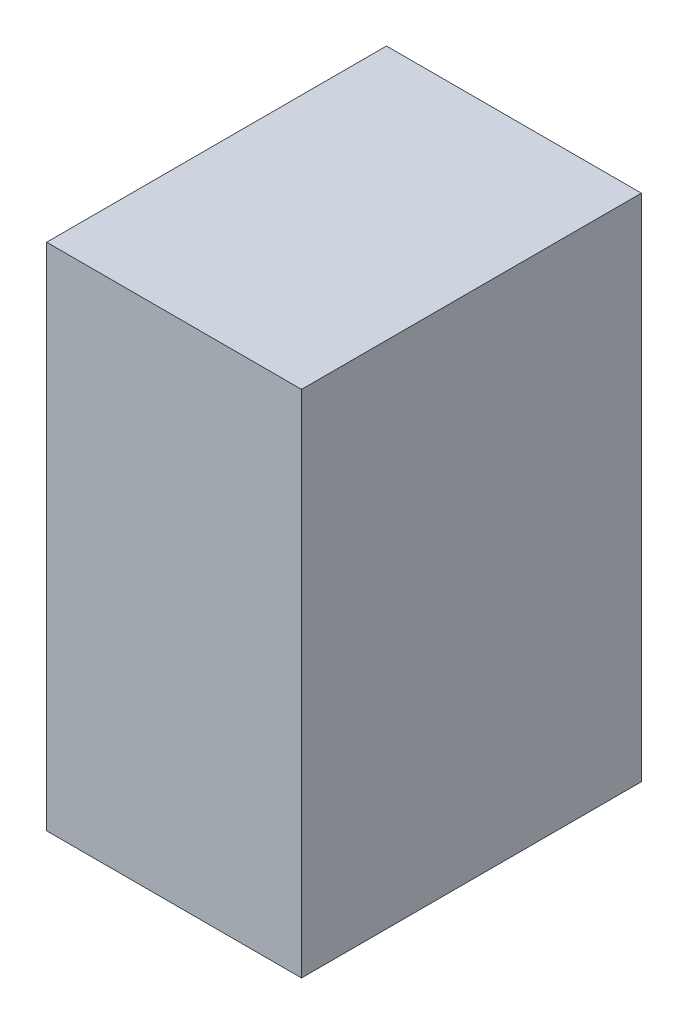
SolidWorks part; units mm, degrees
ref_plane "Alzado" through (0, 0, 0) normal (0, 0, 1) x (1, 0, 0)
ref_plane "Planta" through (0, 0, 0) normal (0, 1, 0) x (1, 0, 0)
ref_plane "Vista lateral" through (0, 0, 0) normal (1, 0, 0) x (0, 0, -1)
sketch "Croquis1" plane through (0, 0, 0) normal (0, 0, 1) x (1, 0, 0)
  line L1 (-3, -6) -> (3, -6)
  line L2 (-3, -6) -> (-3, 6)
  line L3 (-3, 6) -> (3, 6)
  line L4 (3, -6) -> (3, 6)
  line L5 (-3, -6) -> (3, 6) construction
  line L6 (-3, 6) -> (3, -6) construction
  point P0 (0, 0)
  dimension "D1" = 6
  dimension "D2" = 12
extrude "Saliente-Extruir1" add sketch "Croquis1" along normal blind 8
